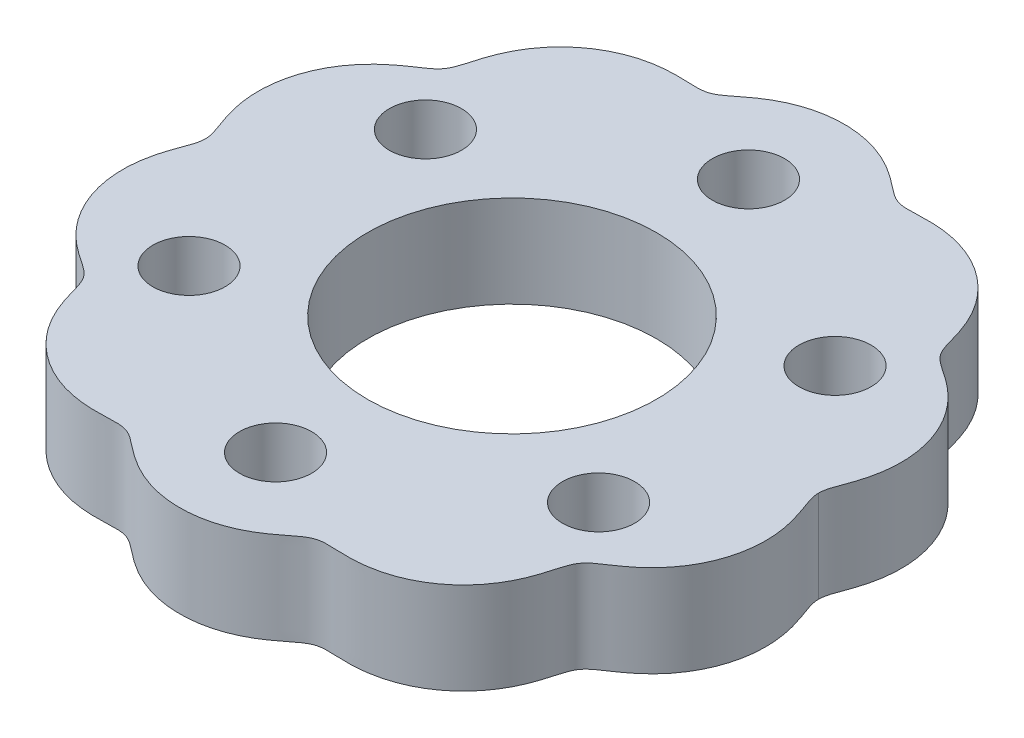
SolidWorks part; units mm, degrees
ref_plane "Front Plane" through (0, 0, 0) normal (0, 0, 1) x (1, 0, 0)
ref_plane "Top Plane" through (0, 0, 0) normal (0, 1, 0) x (1, 0, 0)
ref_plane "Right Plane" through (0, 0, 0) normal (1, 0, 0) x (0, 0, -1)
sketch "Sketch1" plane through (0, 0, 0) normal (0, 1, 0) x (1, 0, 0)
  line L0 (-23.3451, 0) -> (23.3451, 0) construction
  circle A0 centre (0, 0) radius 11
  spline S0 degree 4 poles (24.3121, 6.8167) (24.3482, 6.6335) (24.4096, 6.265) (24.4696, 5.7074) (24.485, 4.9597) (24.436, 4.2136) (24.324, 3.4743) (24.1739, 2.8376) (24.0123, 2.3011) (23.8608, 1.8595) (23.7488, 1.5526) (23.6517, 1.2899) (23.5753, 1.0769) (23.5196, 0.9137) (23.4699, 0.7561) (23.4272, 0.6035) (23.3948, 0.4648) (23.3722, 0.3434) (23.3576, 0.233) (23.3491, 0.1322) (23.3448, 0.0355) (23.3448, -0.0353) (23.3491, -0.132) (23.3576, -0.2326) (23.3721, -0.3428) (23.3946, -0.4638) (23.4268, -0.6021) (23.4693, -0.7541) (23.5188, -0.9112) (23.5743, -1.074) (23.6505, -1.2866) (23.7474, -1.5489) (23.8593, -1.8554) (24.0108, -2.2962) (24.1723, -2.8319) (24.3227, -3.4676) (24.4351, -4.2057) (24.4972, -5.137) (24.4432, -6.2575) (24.192, -7.545) (23.6552, -8.9444) (22.8851, -10.2307) (21.9047, -11.3642) (20.9401, -12.1634) (20.103, -12.7168) (19.4933, -13.128) (19.1367, -13.4141) (18.8453, -13.7476) (18.6593, -14.0909) (18.5326, -14.4268) (18.4084, -14.8269) (18.2284, -15.481) (17.9485, -16.416) (17.4398, -17.5878) (16.6207, -18.8429) (15.5969, -19.938) (14.3997, -20.84) (13.0647, -21.5218) (11.8113, -21.908) (10.7033, -22.0826) (9.7864, -22.1296) (9.1559, -22.1212) (8.6268, -22.0982) (8.2181, -22.0853) (7.9151, -22.0862) (7.6051, -22.1088) (7.286, -22.167) (6.8464, -22.3321) (6.36, -22.6663) (5.8335, -23.0937) (5.2239, -23.5608) (4.6047, -23.9769) (3.7922, -24.4363) (2.7609, -24.8774) (1.4933, -25.2148) (0, -25.3446) (-1.4934, -25.2148) (-2.7609, -24.8774) (-3.7923, -24.4363) (-4.6046, -23.977) (-5.2242, -23.5607) (-5.7506, -23.1571) (-6.2033, -22.7937) (-6.5605, -22.5303) (-6.8219, -22.3687) (-7.0893, -22.2407) (-7.3347, -22.1583) (-7.6052, -22.1086) (-7.915, -22.0864) (-8.2181, -22.0852) (-8.6268, -22.0983) (-9.1559, -22.1212) (-9.7864, -22.1296) (-10.7033, -22.0826) (-11.8112, -21.908) (-13.0647, -21.5218) (-14.3997, -20.84) (-15.5969, -19.938) (-16.6207, -18.8429) (-17.4398, -17.5878) (-17.9485, -16.416) (-18.2284, -15.481) (-18.4084, -14.8269) (-18.5326, -14.4268) (-18.6593, -14.0909) (-18.8453, -13.7476) (-19.1367, -13.4141) (-19.4933, -13.128) (-20.103, -12.7168) (-20.9401, -12.1634) (-21.9047, -11.3642) (-22.8851, -10.2307) (-23.6552, -8.9444) (-24.192, -7.545) (-24.4432, -6.2575) (-24.4972, -5.137) (-24.4351, -4.2057) (-24.3227, -3.4676) (-24.1723, -2.8319) (-24.0108, -2.2962) (-23.8593, -1.8554) (-23.7474, -1.5489) (-23.6505, -1.2866) (-23.5743, -1.074) (-23.5188, -0.9112) (-23.4693, -0.7541) (-23.4268, -0.6021) (-23.3946, -0.4638) (-23.3721, -0.3428) (-23.3576, -0.2326) (-23.3491, -0.132) (-23.3448, -0.0353) (-23.3448, 0.0355) (-23.3491, 0.1322) (-23.3576, 0.233) (-23.3722, 0.3434) (-23.3948, 0.4648) (-23.4272, 0.6035) (-23.4699, 0.7561) (-23.5196, 0.9137) (-23.5753, 1.0769) (-23.6359, 1.246) (-23.7002, 1.4213) (-23.7808, 1.6403) (-23.876, 1.9037) (-24.0123, 2.3011) (-24.1739, 2.8376) (-24.324, 3.4743) (-24.436, 4.2136) (-24.485, 4.9597) (-24.4696, 5.7074) (-24.4096, 6.265) (-24.3482, 6.6335) (-24.3121, 6.8167) knots 0 0 0 0 0 0.007937 0.015874 0.023812 0.031749 0.039686 0.047624 0.051592 0.05556 0.059529 0.061513 0.063497 0.065179 0.06686 0.068542 0.070223 0.071215 0.072207 0.073199 0.074191 0.075181 0.076172 0.077162 0.078153 0.079828 0.081503 0.083178 0.084852 0.086834 0.088815 0.092778 0.09674 0.100703 0.108629 0.116555 0.12448 0.132405 0.148257 0.164108 0.179959 0.19581 0.211662 0.227513 0.232984 0.238454 0.242931 0.24689 0.251683 0.254934 0.258184 0.264686 0.280537 0.296388 0.31224 0.328091 0.343943 0.359794 0.375645 0.38357 0.391496 0.39879 0.402438 0.406085 0.408877 0.411669 0.41563 0.419842 0.428669 0.436595 0.44452 0.452446 0.460371 0.476223 0.492074 0.507926 0.523777 0.539629 0.547554 0.55548 0.563405 0.571331 0.575744 0.580158 0.582264 0.58437 0.588331 0.591123 0.593915 0.597562 0.60121 0.608504 0.61643 0.624355 0.640206 0.656057 0.671909 0.68776 0.703612 0.719463 0.735314 0.741816 0.745066 0.748317 0.75311 0.757069 0.761546 0.767016 0.772487 0.788338 0.80419 0.820041 0.835892 0.851743 0.867595 0.87552 0.883445 0.891371 0.899297 0.90326 0.907222 0.911185 0.913166 0.915148 0.916822 0.918497 0.920172 0.921847 0.922838 0.923828 0.924819 0.925809 0.926801 0.927793 0.928785 0.929777 0.931458 0.93314 0.934821 0.936503 0.938487 0.940471 0.942455 0.94444 0.948408 0.952376 0.960314 0.968251 0.976188 0.984126 0.992063 1 1 1 1 1 construction
  spline S1 degree 4 poles (23.3451, 0) (23.3451, -0.0198) (23.3459, -0.0595) (23.3491, -0.132) (23.3576, -0.2326) (23.3721, -0.3428) (23.3946, -0.4638) (23.4268, -0.6021) (23.4693, -0.7541) (23.5188, -0.9112) (23.5743, -1.074) (23.6505, -1.2866) (23.7474, -1.5489) (23.8593, -1.8554) (24.0108, -2.2962) (24.1723, -2.8319) (24.3227, -3.4676) (24.4351, -4.2057) (24.4972, -5.137) (24.4432, -6.2575) (24.192, -7.545) (23.6552, -8.9444) (22.8851, -10.2307) (21.9047, -11.3642) (20.9401, -12.1634) (20.103, -12.7168) (19.4933, -13.128) (19.1367, -13.4141) (18.8453, -13.7476) (18.6593, -14.0909) (18.5326, -14.4268) (18.4084, -14.8269) (18.2284, -15.481) (17.9485, -16.416) (17.4398, -17.5878) (16.6207, -18.8429) (15.5969, -19.938) (14.3997, -20.84) (13.0647, -21.5218) (11.8113, -21.908) (10.7033, -22.0826) (9.7864, -22.1296) (9.1559, -22.1212) (8.6268, -22.0982) (8.2181, -22.0853) (7.9151, -22.0862) (7.6051, -22.1088) (7.286, -22.167) (6.8464, -22.3321) (6.36, -22.6663) (5.8335, -23.0937) (5.2239, -23.5608) (4.6047, -23.9769) (3.7922, -24.4363) (2.7609, -24.8774) (1.4933, -25.2148) (0, -25.3446) (-1.4934, -25.2148) (-2.7609, -24.8774) (-3.7923, -24.4363) (-4.6046, -23.977) (-5.2242, -23.5607) (-5.7506, -23.1571) (-6.2033, -22.7937) (-6.5605, -22.5303) (-6.8219, -22.3687) (-7.0893, -22.2407) (-7.3347, -22.1583) (-7.6052, -22.1086) (-7.915, -22.0864) (-8.2181, -22.0852) (-8.6268, -22.0983) (-9.1559, -22.1212) (-9.7864, -22.1296) (-10.7033, -22.0826) (-11.8112, -21.908) (-13.0647, -21.5218) (-14.3997, -20.84) (-15.5969, -19.938) (-16.6207, -18.8429) (-17.4398, -17.5878) (-17.9485, -16.416) (-18.2284, -15.481) (-18.4084, -14.8269) (-18.5326, -14.4268) (-18.6593, -14.0909) (-18.8453, -13.7476) (-19.1367, -13.4141) (-19.4933, -13.128) (-20.103, -12.7168) (-20.9401, -12.1634) (-21.9047, -11.3642) (-22.8851, -10.2307) (-23.6552, -8.9444) (-24.192, -7.545) (-24.4432, -6.2575) (-24.4972, -5.137) (-24.4351, -4.2057) (-24.3227, -3.4676) (-24.1723, -2.8319) (-24.0108, -2.2962) (-23.8593, -1.8554) (-23.7474, -1.5489) (-23.6505, -1.2866) (-23.5743, -1.074) (-23.5188, -0.9112) (-23.4693, -0.7541) (-23.4268, -0.6021) (-23.3946, -0.4638) (-23.3721, -0.3428) (-23.3576, -0.2326) (-23.3491, -0.132) (-23.3459, -0.0595) (-23.3451, -0.0198) (-23.3451, 0) knots 0.074191 0.074191 0.074191 0.074191 0.074191 0.075181 0.076172 0.077162 0.078153 0.079828 0.081503 0.083178 0.084852 0.086834 0.088815 0.092778 0.09674 0.100703 0.108629 0.116555 0.12448 0.132405 0.148257 0.164108 0.179959 0.19581 0.211662 0.227513 0.232984 0.238454 0.242931 0.24689 0.251683 0.254934 0.258184 0.264686 0.280537 0.296388 0.31224 0.328091 0.343943 0.359794 0.375645 0.38357 0.391496 0.39879 0.402438 0.406085 0.408877 0.411669 0.41563 0.419842 0.428669 0.436595 0.44452 0.452446 0.460371 0.476223 0.492074 0.507926 0.523777 0.539629 0.547554 0.55548 0.563405 0.571331 0.575744 0.580158 0.582264 0.58437 0.588331 0.591123 0.593915 0.597562 0.60121 0.608504 0.61643 0.624355 0.640206 0.656057 0.671909 0.68776 0.703612 0.719463 0.735314 0.741816 0.745066 0.748317 0.75311 0.757069 0.761546 0.767016 0.772487 0.788338 0.80419 0.820041 0.835892 0.851743 0.867595 0.87552 0.883445 0.891371 0.899297 0.90326 0.907222 0.911185 0.913166 0.915148 0.916822 0.918497 0.920172 0.921847 0.922838 0.923828 0.924819 0.925809 0.925809 0.925809 0.925809 0.925809
  spline S2 degree 4 poles (23.3451, 0) (23.3451, 0.0198) (23.3459, 0.0595) (23.3491, 0.132) (23.3576, 0.2326) (23.3721, 0.3428) (23.3946, 0.4638) (23.4268, 0.6021) (23.4693, 0.7541) (23.5188, 0.9112) (23.5743, 1.074) (23.6505, 1.2866) (23.7474, 1.5489) (23.8593, 1.8554) (24.0108, 2.2962) (24.1723, 2.8319) (24.3227, 3.4676) (24.4351, 4.2057) (24.4972, 5.137) (24.4432, 6.2575) (24.192, 7.545) (23.6552, 8.9444) (22.8851, 10.2307) (21.9047, 11.3642) (20.9401, 12.1634) (20.103, 12.7168) (19.4933, 13.128) (19.1367, 13.4141) (18.8453, 13.7476) (18.6593, 14.0909) (18.5326, 14.4268) (18.4084, 14.8269) (18.2284, 15.481) (17.9485, 16.416) (17.4398, 17.5878) (16.6207, 18.8429) (15.5969, 19.938) (14.3997, 20.84) (13.0647, 21.5218) (11.8113, 21.908) (10.7033, 22.0826) (9.7864, 22.1296) (9.1559, 22.1212) (8.6268, 22.0982) (8.2181, 22.0853) (7.9151, 22.0862) (7.6051, 22.1088) (7.286, 22.167) (6.8464, 22.3321) (6.36, 22.6663) (5.8335, 23.0937) (5.2239, 23.5608) (4.6047, 23.9769) (3.7922, 24.4363) (2.7609, 24.8774) (1.4933, 25.2148) (0, 25.3446) (-1.4934, 25.2148) (-2.7609, 24.8774) (-3.7923, 24.4363) (-4.6046, 23.977) (-5.2242, 23.5607) (-5.7506, 23.1571) (-6.2033, 22.7937) (-6.5605, 22.5303) (-6.8219, 22.3687) (-7.0893, 22.2407) (-7.3347, 22.1583) (-7.6052, 22.1086) (-7.915, 22.0864) (-8.2181, 22.0852) (-8.6268, 22.0983) (-9.1559, 22.1212) (-9.7864, 22.1296) (-10.7033, 22.0826) (-11.8112, 21.908) (-13.0647, 21.5218) (-14.3997, 20.84) (-15.5969, 19.938) (-16.6207, 18.8429) (-17.4398, 17.5878) (-17.9485, 16.416) (-18.2284, 15.481) (-18.4084, 14.8269) (-18.5326, 14.4268) (-18.6593, 14.0909) (-18.8453, 13.7476) (-19.1367, 13.4141) (-19.4933, 13.128) (-20.103, 12.7168) (-20.9401, 12.1634) (-21.9047, 11.3642) (-22.8851, 10.2307) (-23.6552, 8.9444) (-24.192, 7.545) (-24.4432, 6.2575) (-24.4972, 5.137) (-24.4351, 4.2057) (-24.3227, 3.4676) (-24.1723, 2.8319) (-24.0108, 2.2962) (-23.8593, 1.8554) (-23.7474, 1.5489) (-23.6505, 1.2866) (-23.5743, 1.074) (-23.5188, 0.9112) (-23.4693, 0.7541) (-23.4268, 0.6021) (-23.3946, 0.4638) (-23.3721, 0.3428) (-23.3576, 0.2326) (-23.3491, 0.132) (-23.3459, 0.0595) (-23.3451, 0.0198) (-23.3451, 0) knots 0.074191 0.074191 0.074191 0.074191 0.074191 0.075181 0.076172 0.077162 0.078153 0.079828 0.081503 0.083178 0.084852 0.086834 0.088815 0.092778 0.09674 0.100703 0.108629 0.116555 0.12448 0.132405 0.148257 0.164108 0.179959 0.19581 0.211662 0.227513 0.232984 0.238454 0.242931 0.24689 0.251683 0.254934 0.258184 0.264686 0.280537 0.296388 0.31224 0.328091 0.343943 0.359794 0.375645 0.38357 0.391496 0.39879 0.402438 0.406085 0.408877 0.411669 0.41563 0.419842 0.428669 0.436595 0.44452 0.452446 0.460371 0.476223 0.492074 0.507926 0.523777 0.539629 0.547554 0.55548 0.563405 0.571331 0.575744 0.580158 0.582264 0.58437 0.588331 0.591123 0.593915 0.597562 0.60121 0.608504 0.61643 0.624355 0.640206 0.656057 0.671909 0.68776 0.703612 0.719463 0.735314 0.741816 0.745066 0.748317 0.75311 0.757069 0.761546 0.767016 0.772487 0.788338 0.80419 0.820041 0.835892 0.851743 0.867595 0.87552 0.883445 0.891371 0.899297 0.90326 0.907222 0.911185 0.913166 0.915148 0.916822 0.918497 0.920172 0.921847 0.922838 0.923828 0.924819 0.925809 0.925809 0.925809 0.925809 0.925809
  dimension "D1" = 22
extrude "Boss-Extrude1" add sketch "Sketch1" along normal blind 7
sketch "Sketch2" plane through (0, 7, 0) normal (0, 1, 0) x (1, 0, 0)
  circle A0 centre (0, 18) radius 2.75
  circle A10 centre (15.5885, 9) radius 2.75
  circle A11 centre (15.5885, -9) radius 2.75
  circle A12 centre (0, -18) radius 2.75
  circle A13 centre (-15.5885, -9) radius 2.75
  circle A14 centre (-15.5885, 9) radius 2.75
  point P16 (0, 0)
  point P24 (0, 0)
  dimension "D2" = 5.5
  dimension "D1" = 18
  dimension "D3" = 6
extrude "Cut-Extrude1" cut sketch "Sketch2" against normal through all
